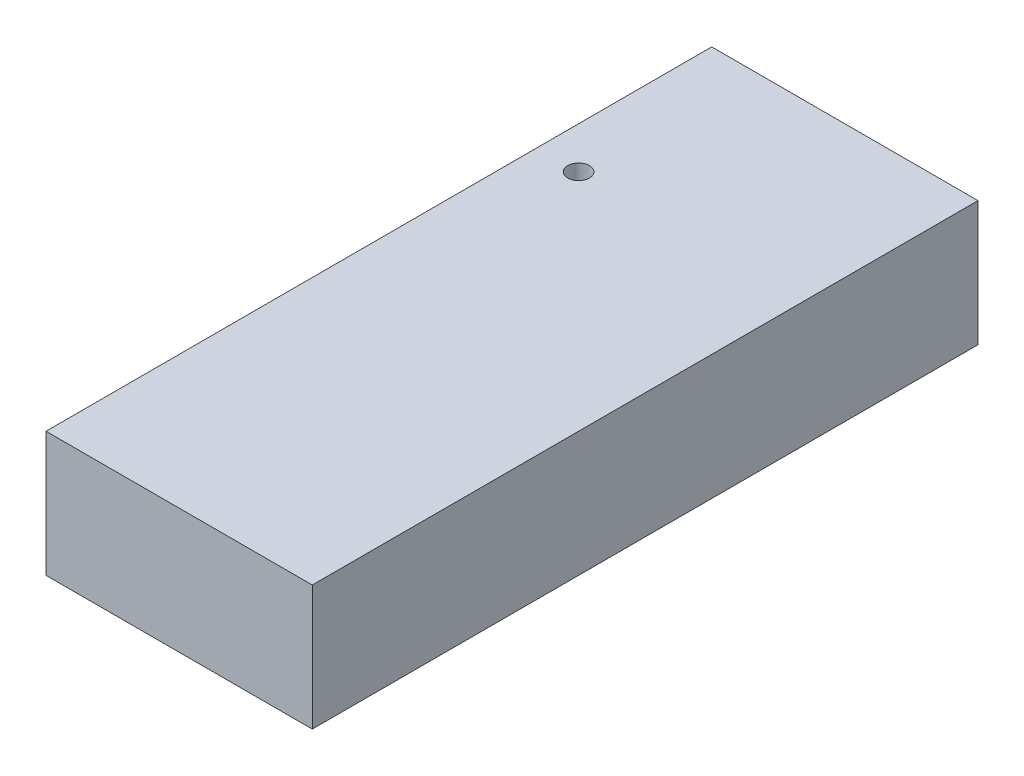
SolidWorks part; units mm, degrees
ref_plane "Front Plane" through (0, 0, 0) normal (0, 0, 1) x (1, 0, 0)
ref_plane "Top Plane" through (0, 0, 0) normal (0, 1, 0) x (1, 0, 0)
ref_plane "Right Plane" through (0, 0, 0) normal (1, 0, 0) x (0, 0, -1)
sketch "Sketch1" plane through (0, 0, 0) normal (0, 1, 0) x (1, 0, 0)
  line L1 (0, 0) -> (20.32, 0)
  line L2 (0, 0) -> (0, 50.8)
  line L3 (0, 50.8) -> (20.32, 50.8)
  line L4 (20.32, 0) -> (20.32, 50.8)
  dimension "D1" = 50.8
  dimension "D2" = 20.32
extrude "Boss-Extrude1" add sketch "Sketch1" along normal blind 9.525
sketch "Sketch2" plane through (0, 9.525, 0) normal (0, 1, 0) x (1, 0, 0)
  line L0 (0, 0) -> (20.32, 0) construction
  line L1 (0, 50.8) -> (0, 0) construction
  circle A0 centre (3.175, 37.465) radius 0.8255
  dimension "D2" = 1.651
  dimension "D1" = 37.465
  dimension "D3" = 3.175
extrude "Cut-Extrude1" cut sketch "Sketch2" against normal through all
